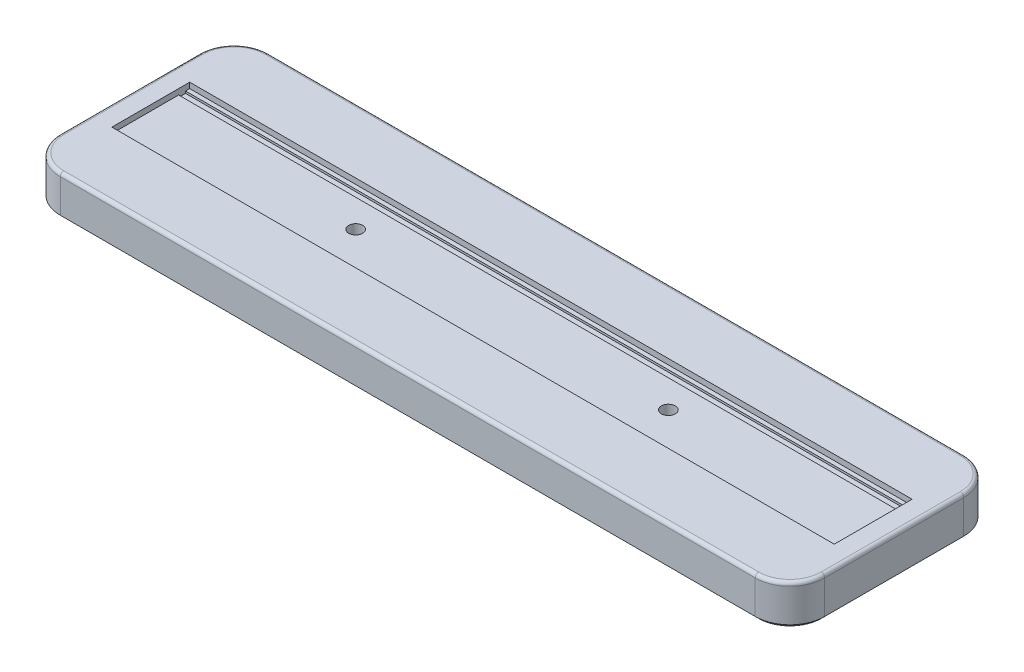
SolidWorks part; units mm, degrees
ref_plane "Front Plane" through (0, 0, 0) normal (0, 0, 1) x (1, 0, 0)
ref_plane "Top Plane" through (0, 0, 0) normal (0, 1, 0) x (1, 0, 0)
ref_plane "Right Plane" through (0, 0, 0) normal (1, 0, 0) x (0, 0, -1)
sketch "Sketch1" plane through (0, 0, 0) normal (0, 1, 0) x (1, 0, 0)
  line L0 (-45, 0) -> (45, 0) construction
  line L2 (-103.95, -11.2) -> (103.95, -11.2)
  line L3 (-103.95, -11.2) -> (-103.95, 11.2)
  line L4 (-103.95, 11.2) -> (103.95, 11.2)
  line L5 (103.95, -11.2) -> (103.95, 11.2)
  line L6 (-103.95, -11.2) -> (103.95, 11.2) construction
  line L7 (-103.95, 11.2) -> (103.95, -11.2) construction
  circle A0 centre (-45, 0) radius 2
  circle A1 centre (45, 0) radius 2
  point P4 (0, 0)
  point P5 (0, 0)
  dimension "D1" = 4
  dimension "D2" = 90
  dimension "D3" = 207.9
  dimension "D4" = 22.4
extrude "Boss-Extrude1" add sketch "Sketch1" along normal blind 10
sketch "Sketch2" plane through (0, 0, 0) normal (0, -1, 0) x (1, 0, 0)
  line L1 (-110, -30) -> (110, -30)
  line L2 (-110, -30) -> (-110, 30)
  line L3 (-110, 30) -> (110, 30)
  line L4 (110, -30) -> (110, 30)
  line L5 (-110, -30) -> (110, 30) construction
  line L6 (-110, 30) -> (110, -30) construction
  line L7 (-103.95, 11.2) -> (103.95, 11.2)
  line L8 (-103.95, 11.2) -> (-103.95, -11.2)
  line L9 (-103.95, -11.2) -> (103.95, -11.2)
  line L10 (103.95, 11.2) -> (103.95, -11.2)
  point P0 (0, 0)
  dimension "D1" = 220
  dimension "D2" = 60
extrude "Boss-Extrude2" add sketch "Sketch2" against normal offset from surface (11.6 mm away) 1.6 up to face at (0, 10, 0) offset beyond the face yes
fillet "Fillet1" radius 10 4 edges at (-110, 5.8, 30) (-110, 5.8, -30) (110, 5.8, 30) (110, 5.8, -30)
fillet "Fillet2" radius 1 8 edges at (107.0711, 11.6, -27.0711) (110, 11.6, 0) (107.0711, 11.6, 27.0711) (0, 11.6, 30) (-107.0711, 11.6, 27.0711) (-110, 11.6, 0) (-107.0711, 11.6, -27.0711) (0, 11.6, -30)
chamfer "Chamfer1" distance 1 angle 45 10 edges at (107.0711, 0, 27.0711) (110, 0, 0) (107.0711, 0, -27.0711) (0, 0, -30) (-107.0711, 0, -27.0711) (-110, 0, 0) (-107.0711, 0, 27.0711) (0, 0, 30) (45, 0, 2) (-45, 0, 2)
sketch "Sketch3" plane through (0, 10, 0) normal (0, 1, 0) x (1, 0, 0)
  line L0 (-103.95, 11.2) -> (-103.95, -11.2) construction
  line L1 (-103.95, 10) -> (103.95, 10)
  line L2 (-103.95, 10) -> (-103.95, 8)
  line L3 (-103.95, 8) -> (103.95, 8)
  line L4 (103.95, 10) -> (103.95, 8)
  line L5 (103.95, -11.2) -> (103.95, 11.2) construction
  circle A0 centre (-45, 0) radius 2 construction
  dimension "D2" = 8
  dimension "D1" = 2
extrude "Cut-Extrude1" cut sketch "Sketch3" against normal blind 0.6
